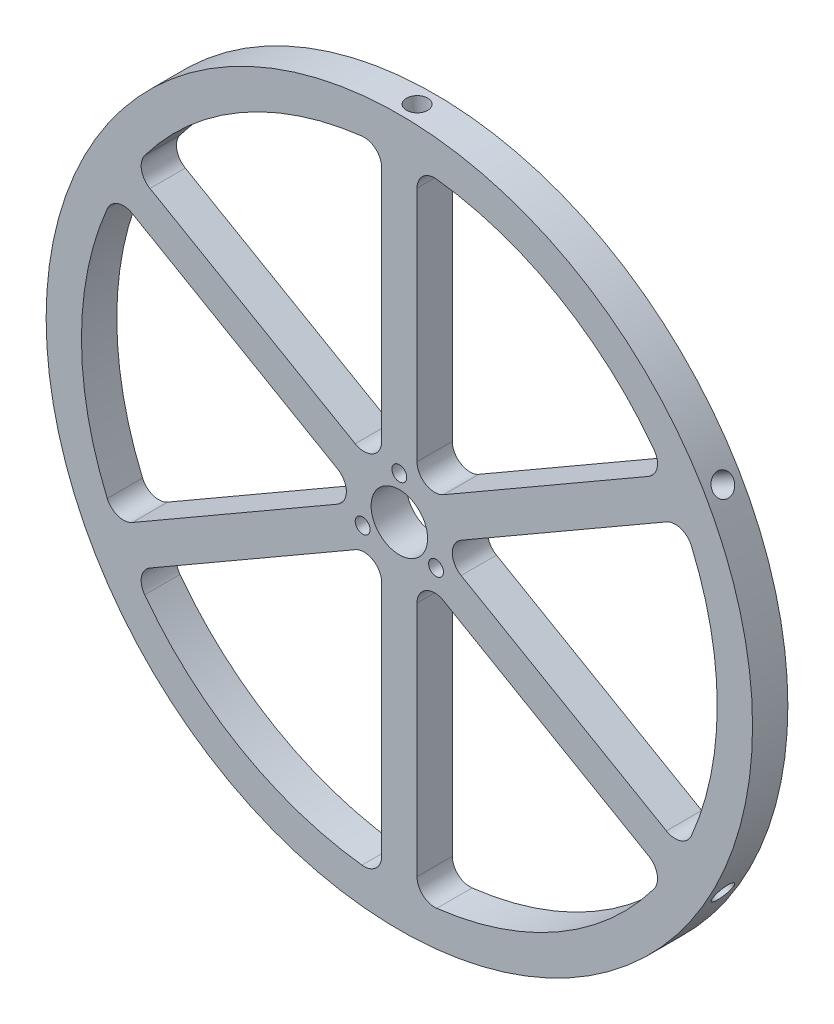
SolidWorks part; units mm, degrees
ref_plane "Front" through (0, 0, 0) normal (0, 0, 1) x (1, 0, 0)
ref_plane "Top" through (0, 0, 0) normal (0, 1, 0) x (1, 0, 0)
ref_plane "Right" through (0, 0, 0) normal (1, 0, 0) x (0, 0, -1)
sketch "Esquisse1" plane through (0, 0, 0) normal (0, 0, 1) x (1, 0, 0)
  circle A0 centre (0, 0) radius 100
  dimension "D1" = 200
extrude "Boss.-Extru.1" add sketch "Esquisse1" along normal blind 10
sketch "Esquisse2" plane through (0, 0, 10) normal (0, 0, 1) x (1, 0, 0)
  line L0 (0, 0) -> (10, 0) construction
  line L1 (10, 0) -> (80.3219, 40.6004)
  line L2 (80, 0) -> (10, 0) construction
  line L3 (10, 0) -> (80.3219, -40.6004)
  line L4 (5, -8.6603) -> (75.3219, -49.2606)
  line L5 (5, -8.6603) -> (5, -89.861)
  line L6 (0, 0) -> (5, -8.6603) construction
  line L7 (40, -69.282) -> (5, -8.6603) construction
  line L8 (-5, -8.6603) -> (-5, -89.861)
  line L9 (-5, -8.6603) -> (-75.3219, -49.2606)
  line L10 (0, 0) -> (-5, -8.6603) construction
  line L11 (-40, -69.282) -> (-5, -8.6603) construction
  line L12 (-10, 0) -> (-80.3219, -40.6004)
  line L13 (-10, 0) -> (-80.3219, 40.6004)
  line L14 (0, 0) -> (-10, 0) construction
  line L15 (-80, 0) -> (-10, 0) construction
  line L16 (-5, 8.6603) -> (-75.3219, 49.2606)
  line L17 (-5, 8.6603) -> (-5, 89.861)
  line L18 (0, 0) -> (-5, 8.6603) construction
  line L19 (-40, 69.282) -> (-5, 8.6603) construction
  line L20 (5, 8.6603) -> (5, 89.861)
  line L21 (5, 8.6603) -> (75.3219, 49.2606)
  line L22 (0, 0) -> (5, 8.6603) construction
  line L23 (40, 69.282) -> (5, 8.6603) construction
  arc A0 (80.3219, 40.6004) -> (80.3219, -40.6004) centre (0, 0) cw
  circle A1 centre (0, 0) radius 100 construction
  arc A2 (75.3219, -49.2606) -> (5, -89.861) centre (0, 0) cw
  arc A3 (-5, -89.861) -> (-75.3219, -49.2606) centre (0, 0) cw
  arc A4 (-80.3219, -40.6004) -> (-80.3219, 40.6004) centre (0, 0) cw
  arc A5 (-75.3219, 49.2606) -> (-5, 89.861) centre (0, 0) cw
  arc A6 (5, 89.861) -> (75.3219, 49.2606) centre (0, 0) cw
  point P30 (0, 0)
  dimension "D1" = 10
  dimension "D3" = 10
  dimension "D2" = 6
extrude "Enlèv. mat.-Extru.1" cut sketch "Esquisse2" against normal through all both and the other way through all
fillet "Congé1" radius 5 18 edges at (-5, 8.6603, 5) (-10, 0, 5) (-5, -8.6603, 5) (5, -8.6603, 5) (10, 0, 5) (80.3219, 40.6004, 5) (80.3219, -40.6004, 5) (75.3219, -49.2606, 5) (5, -89.861, 5) (-5, -89.861, 5) (-75.3219, -49.2606, 5) (-80.3219, -40.6004, 5) (-80.3219, 40.6004, 5) (-75.3219, 49.2606, 5) (-5, 89.861, 5) (5, 89.861, 5) (75.3219, 49.2606, 5) (5, 8.6603, 5)
sketch "Esquisse3" plane through (0, 0, 10) normal (0, 0, 1) x (1, 0, 0)
  circle A0 centre (0, 0) radius 8
  dimension "D1" = 16
extrude "Enlèv. mat.-Extru.2" cut sketch "Esquisse3" against normal through all both and the other way through all
sketch "Esquisse4" plane through (0, 0, 10) normal (0, 0, 1) x (1, 0, 0)
  line L0 (0, 0) -> (0, 12) construction
  line L1 (0, 0) -> (-10.3923, -6) construction
  line L2 (0, 0) -> (10.3923, -6) construction
  circle A0 centre (0, 12) radius 2.1
  circle A2 centre (10.3923, -6) radius 2.1
  circle A3 centre (-10.3923, -6) radius 2.1
  dimension "D1" = 4.2
  dimension "D2" = 12
  dimension "D3" = 120
  dimension "D4" = 120
extrude "Enlèv. mat.-Extru.3" cut sketch "Esquisse4" against normal through all both and the other way through all
sketch "Esquisse5" plane through (0, 0, 0) normal (0, 1, 0) x (0, 0, -1)
  line L0 (0, 0) -> (-10, 0) construction
  line L1 (0, -100) -> (0, 100) construction
  line L2 (-10, 100) -> (-10, -100) construction
  circle A0 centre (-5, 0) radius 3
  dimension "D1" = 6
extrude "Enlèv. mat.-Extru.4" cut sketch "Esquisse5" against normal blind 10 from offset 100
pattern_circular "Répétition circulaire1" count 6 over 360 about axis through (0, 0, 0) along (0, 0, 1) of "Enlèv. mat.-Extru.4"
